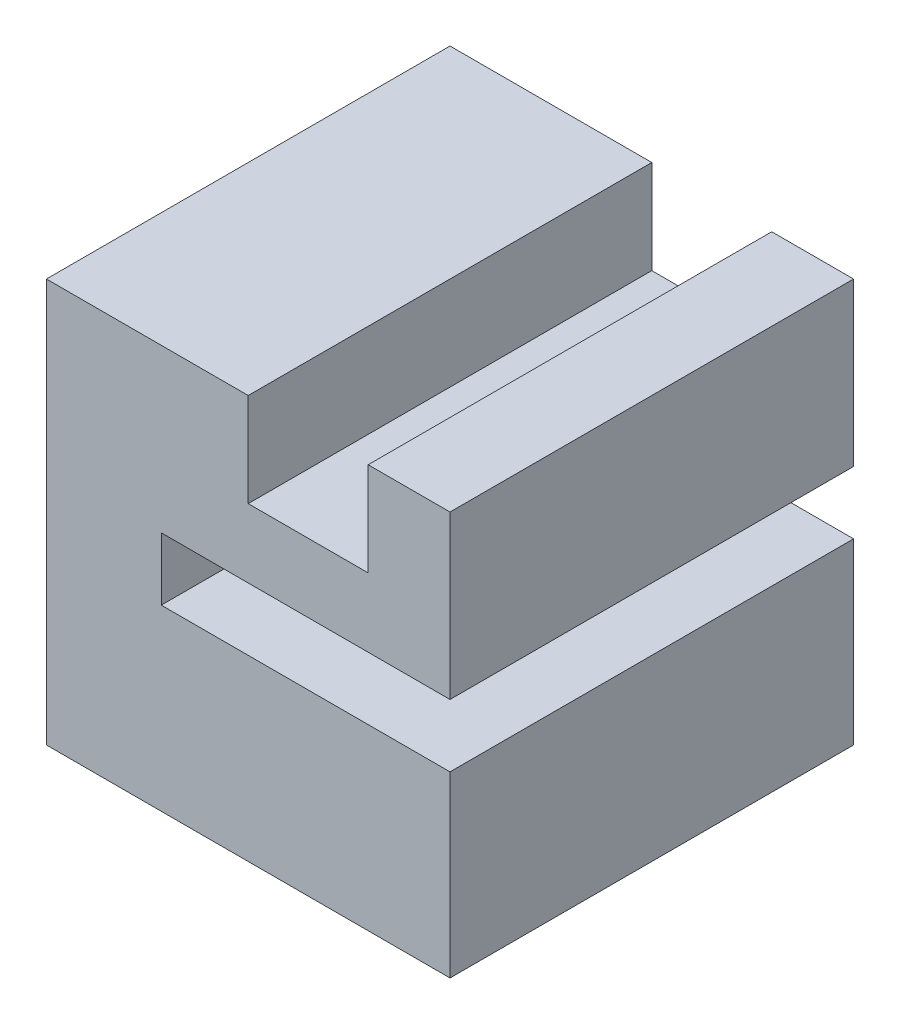
SolidWorks part; units mm, degrees
ref_plane "Plan de face" through (0, 0, 0) normal (0, 0, 1) x (1, 0, 0)
ref_plane "Plan de dessus" through (0, 0, 0) normal (0, 1, 0) x (1, 0, 0)
ref_plane "Plan de droite" through (0, 0, 0) normal (1, 0, 0) x (0, 0, -1)
sketch "Esquisse1" plane through (0, 0, 0) normal (0, 0, 1) x (1, 0, 0)
  line L1 (0, 0) -> (40, 0)
  line L2 (0, 0) -> (0, 40)
  line L3 (0, 40) -> (40, 40)
  line L4 (40, 0) -> (40, 40)
  dimension "D1" = 40
  dimension "D2" = 40
extrude "Boss.-Extru.1" add sketch "Esquisse1" along normal blind 40
sketch "Esquisse2" plane through (0, 0, 40) normal (0, 0, 1) x (1, 0, 0)
  line L0 (0, 40) -> (0, 0) construction
  line L1 (20, 44.4761) -> (31.8874, 44.4761)
  line L2 (20, 44.4761) -> (20, 30.7187)
  line L3 (20, 30.7187) -> (31.8874, 30.7187)
  line L4 (31.8874, 44.4761) -> (31.8874, 30.7187)
  line L6 (44.2424, 23.9068) -> (11.3849, 23.9068)
  line L7 (44.2424, 23.9068) -> (44.2424, 17.696)
  line L8 (44.2424, 17.696) -> (11.3849, 17.696)
  line L9 (11.3849, 23.9068) -> (11.3849, 17.696)
  dimension "D1" = 20
extrude "Enlèv. mat.-Extru.1" cut sketch "Esquisse2" against normal blind 40
